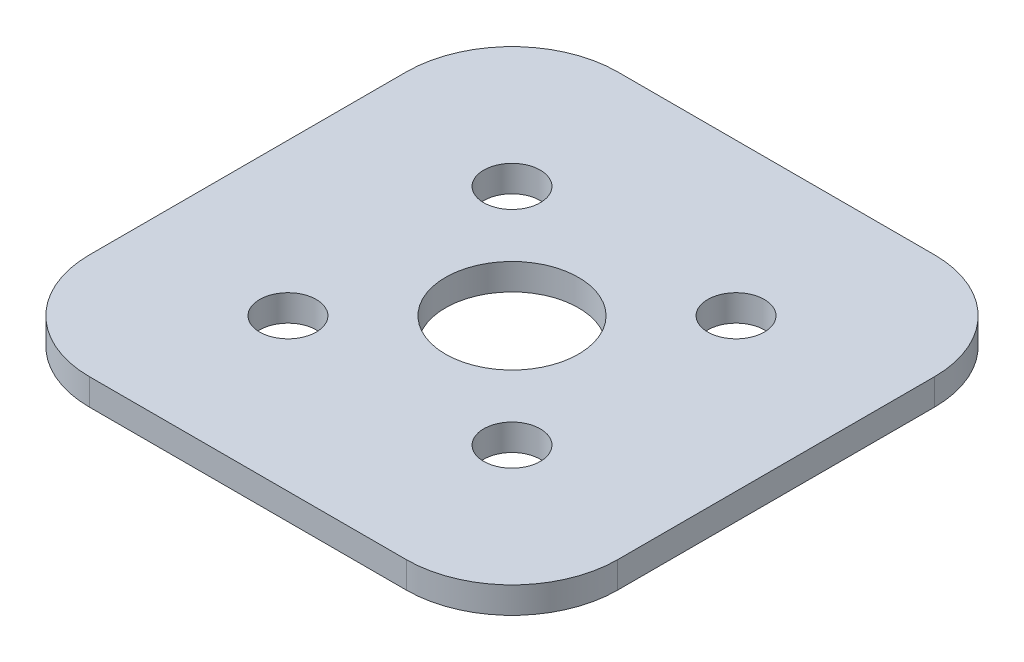
SolidWorks part; units mm, degrees
ref_plane "Front Plane" through (0, 0, 0) normal (0, 0, 1) x (1, 0, 0)
ref_plane "Top Plane" through (0, 0, 0) normal (0, 1, 0) x (1, 0, 0)
ref_plane "Right Plane" through (0, 0, 0) normal (1, 0, 0) x (0, 0, -1)
sketch "Sketch2" plane through (0, 0, 0) normal (0, 1, 0) x (1, 0, 0)
  line L0 (-6.7352, 6.7352) -> (6.7352, -6.7352) construction
  line L1 (-6.7352, -6.7352) -> (6.7352, 6.7352) construction
  line L3 (9.525, -15.875) -> (-9.525, -15.875)
  line L4 (15.875, -9.525) -> (15.875, 9.525)
  line L5 (9.525, 15.875) -> (-9.525, 15.875)
  line L6 (-15.875, -9.525) -> (-15.875, 9.525)
  line L7 (15.875, -15.875) -> (-15.875, 15.875) construction
  line L8 (15.875, 15.875) -> (-15.875, -15.875) construction
  circle A0 centre (0, 0) radius 4
  circle A1 centre (-6.7352, 6.7352) radius 1.7
  circle A2 centre (6.7352, 6.7352) radius 1.7
  circle A3 centre (-6.7352, -6.7352) radius 1.7
  circle A4 centre (6.7352, -6.7352) radius 1.7
  arc A5 (-15.875, 9.525) -> (-9.525, 15.875) centre (-9.525, 9.525) cw
  arc A6 (15.875, 9.525) -> (9.525, 15.875) centre (9.525, 9.525) ccw
  arc A7 (9.525, -15.875) -> (15.875, -9.525) centre (9.525, -9.525) ccw
  arc A8 (-15.875, -9.525) -> (-9.525, -15.875) centre (-9.525, -9.525) ccw
  point P27 (0, 0)
  point P28 (0, 0)
  dimension "D1" = 8
  dimension "D12" = 3.4
  dimension "D13" = 3.4
  dimension "D14" = 3.4
  dimension "D15" = 3.4
  dimension "D16" = 6.35
  dimension "D17" = 6.35
  dimension "D18" = 6.35
  dimension "D19" = 6.35
  dimension "D2" = 13.4704
  dimension "D3" = 9.525
  dimension "D4" = 13.4704
  dimension "D6" = 6.7352
  dimension "D7" = 9.525
  dimension "D8" = 9.525
  dimension "D9" = 13.4704
  dimension "D10" = 13.4704
  dimension "D11" = 31.75
  dimension "D5" = 31.75
extrude "Boss-Extrude1" add sketch "Sketch2" along normal blind 1.5875
equation "\"AluminumScrewHoleDiameter\" = 3.4mm"
equation "\"D12@Sketch2\"=\"AluminumScrewHoleDiameter\""
equation "\"D13@Sketch2\"=\"AluminumScrewHoleDiameter\""
equation "\"D14@Sketch2\"=\"AluminumScrewHoleDiameter\""
equation "\"D15@Sketch2\"=\"AluminumScrewHoleDiameter\""
